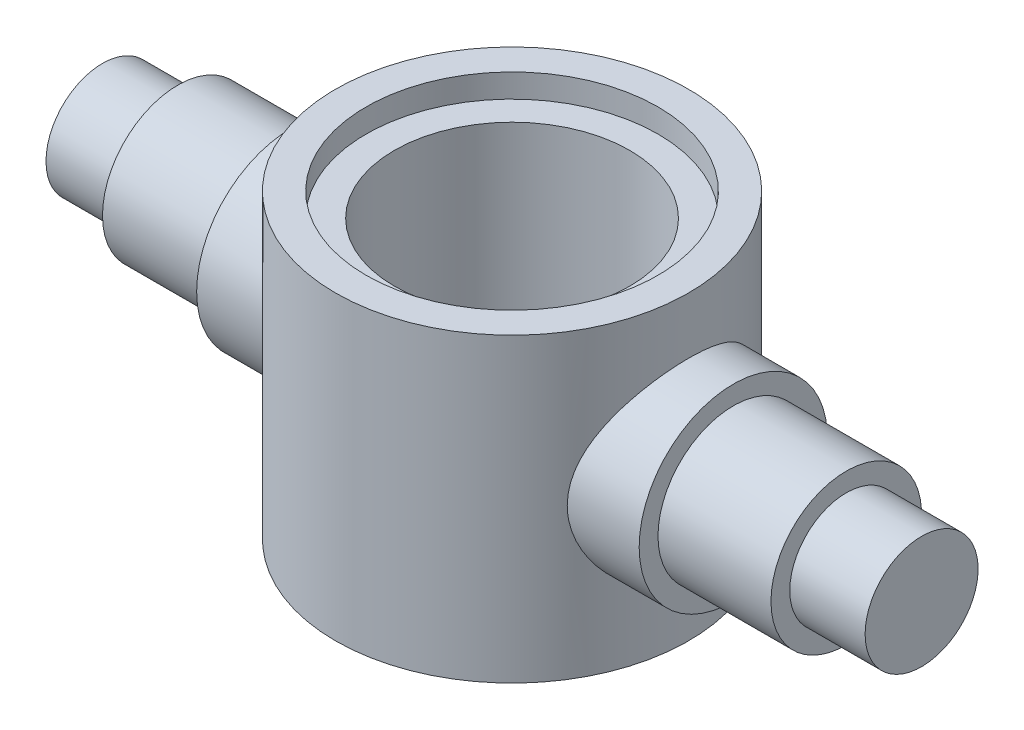
SolidWorks part; units mm, degrees
ref_plane "Front Plane" through (0, 0, 0) normal (0, 0, 1) x (1, 0, 0)
ref_plane "Top Plane" through (0, 0, 0) normal (0, 1, 0) x (1, 0, 0)
ref_plane "Right Plane" through (0, 0, 0) normal (1, 0, 0) x (0, 0, -1)
sketch "Sketch1" plane through (0, 0, 0) normal (0, 1, 0) x (1, 0, 0)
  line L0 (-87, 0) -> (-87, 12)
  line L1 (-87, 12) -> (-71, 12)
  line L2 (-71, 12) -> (-71, 16)
  line L3 (-71, 16) -> (-47, 16)
  line L4 (-47, 16) -> (-47, 20)
  line L5 (0, -55) -> (0, 55) construction
  line L6 (47, 16) -> (47, 20)
  line L7 (71, 16) -> (47, 16)
  line L8 (71, 12) -> (71, 16)
  line L9 (87, 12) -> (71, 12)
  line L10 (87, 0) -> (87, 12)
  line L11 (-47, 20) -> (47, 20)
  line L12 (-87, 0) -> (87, 0)
  dimension "D1" = 94
  dimension "D2" = 24
  dimension "D3" = 16
  dimension "D4" = 20
  dimension "D5" = 16
  dimension "D6" = 12
revolve "Revolve1" add sketch "Sketch1" angle 360 about L12
sketch "Sketch2" plane through (0, 0, 0) normal (0, 1, 0) x (1, 0, 0)
  circle A0 centre (0, 0) radius 37.5
  dimension "D1" = 75
extrude "Boss-Extrude1" add sketch "Sketch2" along normal mid plane 64
hole_wizard "Hole1" positions "Sketch5" profile "Sketch4" legacy end condition through all
sketch "Sketch5" plane through (0, 32, 0) normal (0, 1, 0) x (1, 0, 0)
  point P0 (0, 0)
sketch "Sketch4" plane through (0, 32, 0) normal (1, 0, 0) x (0, 0, 1)
  line L0 (0, 0) -> (0, 64)
  line L1 (0, 64) -> (25, 64)
  line L2 (25, 64) -> (25, 5)
  line L3 (25, 5) -> (31, 5)
  line L4 (31, 5) -> (31, 0)
  line L5 (31, 0) -> (0, 0)
  line L6 (0, 110) -> (0, -10) construction
  dimension "Diameter" = 50
  dimension "Depth" = 64
  dimension "C-Bore Diameter" = 62
  dimension "C-Bore Depth" = 5
